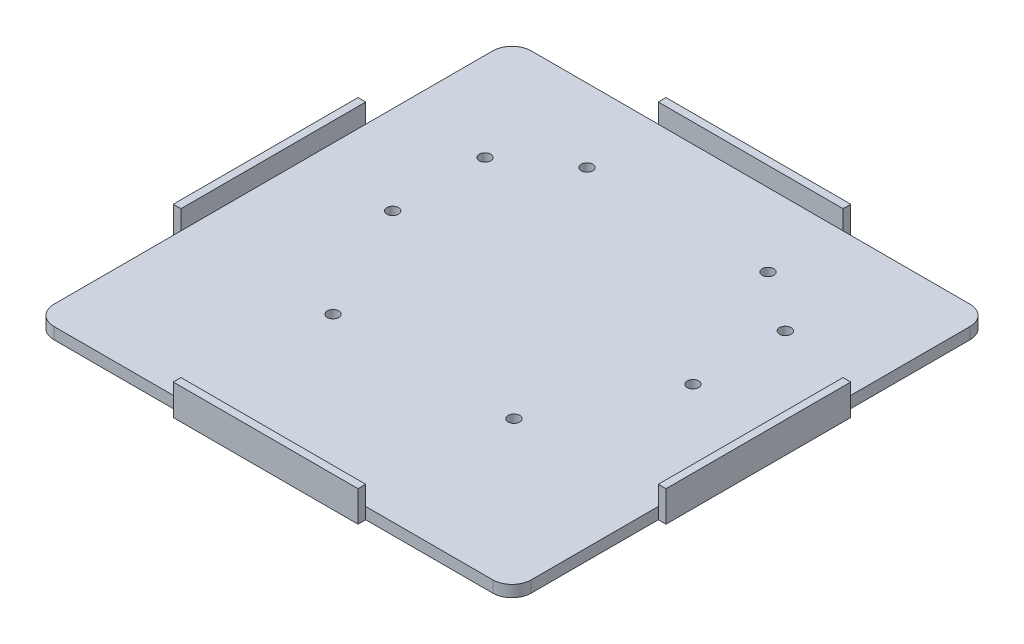
SolidWorks part; units mm, degrees
ref_plane "前视基准面" through (0, 0, 0) normal (0, 0, 1) x (1, 0, 0)
ref_plane "上视基准面" through (0, 0, 0) normal (0, 1, 0) x (1, 0, 0)
ref_plane "右视基准面" through (0, 0, 0) normal (1, 0, 0) x (0, 0, -1)
other "Configuration Table"
sketch "草图1" plane through (0, 0, 0) normal (0, 1, 0) x (1, 0, 0)
  line L1 (-64, 64) -> (64, 64)
  line L2 (-64, 64) -> (-64, -64)
  line L3 (-64, -64) -> (64, -64)
  line L4 (64, 64) -> (64, -64)
  line L5 (-64, 64) -> (64, -64) construction
  line L6 (-64, -64) -> (64, 64) construction
  point P0 (0, 0)
extrude "凸台-拉伸1" add sketch "草图1" along normal blind 8
sketch "草图2" plane through (0, 8, 0) normal (0, 1, 0) x (1, 0, 0)
  line L0 (-67.8405, 62) -> (72.7837, 62) construction
  line L1 (64, 64) -> (-64, 64) construction
  line L2 (-71.2496, 0) -> (72.7837, 0) construction
  line L3 (-67.8405, -62) -> (72.7837, -62) construction
  line L4 (0, 66.3065) -> (0, -71.761) construction
  line L5 (-24, 69.2042) -> (-24, -71.761) construction
  line L6 (-64, 64) -> (-64, -64) construction
  line L7 (24, 71.4201) -> (24, -73.8064) construction
  line L8 (64, -64) -> (64, 64) construction
  line L9 (-62, 69.2042) -> (-62, -69.886) construction
  line L10 (-71.2496, 24) -> (74.9996, 24) construction
  line L11 (-71.2496, -24) -> (74.9996, -24) construction
  line L12 (-64, 64) -> (-64, 24)
  line L13 (-64, 24) -> (-62, 24)
  line L14 (-62, 24) -> (-62, 62)
  line L15 (-62, 62) -> (-24, 62)
  line L16 (-24, 62) -> (-24, 64)
  line L17 (-24, 64) -> (-64, 64)
  line L18 (-64, -24) -> (-62, -24)
  line L19 (-64, -64) -> (-64, -24)
  line L20 (-62, -24) -> (-62, -62)
  line L21 (-62, -62) -> (-24, -62)
  line L22 (-24, -62) -> (-24, -64)
  line L23 (-24, -64) -> (-64, -64)
  line L24 (24, -62) -> (24, -64)
  line L25 (64, 24) -> (62, 24)
  line L26 (24, 62) -> (24, 64)
  line L27 (24, 64) -> (64, 64)
  line L28 (62, 62) -> (24, 62)
  line L29 (64, 64) -> (64, 24)
  line L30 (62, 24) -> (62, 62)
  line L31 (24, -64) -> (64, -64)
  line L32 (62, -62) -> (24, -62)
  line L33 (64, -64) -> (64, -24)
  line L34 (64, -24) -> (62, -24)
  line L35 (62, -24) -> (62, -62)
  dimension "D1" = 2
  dimension "D2" = 40
  dimension "D3" = 40
  dimension "D4" = 2
  dimension "D5" = 40
extrude "切除-拉伸1" cut sketch "草图2" against normal blind 8
sketch "草图3" plane through (0, 8, 0) normal (0, 1, 0) x (1, 0, 0)
  line L0 (-62, 62) -> (62, 62) construction
  line L1 (62, 62) -> (62, -62) construction
  line L2 (62, -62) -> (-62, -62) construction
  line L3 (-62, -62) -> (-62, 62) construction
  line L4 (-62, 62) -> (62, 62)
  line L5 (62, 62) -> (62, -62)
  line L6 (62, -62) -> (-62, -62)
  line L7 (-62, -62) -> (-62, 62)
extrude "切除-拉伸2" cut sketch "草图3" against normal blind 5
fillet "圆角1" radius 5 1 edges at (-62, 1.5, 62)
fillet "圆角2" radius 5 1 edges at (62, 1.5, 62)
fillet "圆角3" radius 5 1 edges at (62, 1.5, -62)
fillet "圆角4" radius 5 1 edges at (-62, 1.5, -62)
sketch "草图4" plane through (0, 0, 0) normal (0, -1, 0) x (1, 0, 0)
  line L0 (0, 68.6928) -> (0, -70.2269) construction
  line L1 (-23.5, 68.6928) -> (-23.5, -72.7837) construction
  line L2 (23.5, 68.6928) -> (23.5, -72.7837) construction
  line L3 (-75.6814, -43) -> (75.3405, -43) construction
  line L4 (-57, -62) -> (-24, -62) construction
  line L5 (-73.8064, 23) -> (79.2609, 23) construction
  line L6 (-39, 68.6928) -> (-39, -72.7837) construction
  line L8 (-88.8063, -32) -> (75.3405, -32) construction
  line L9 (-88.8063, -8) -> (86.2495, -8) construction
  circle A0 centre (-23.5, -43) radius 1.5
  circle A1 centre (23.5, -43) radius 1.5
  circle A2 centre (-23.5, 23) radius 1.5
  circle A3 centre (23.5, 23) radius 1.5
  circle A6 centre (-39, -32) radius 1.5
  circle A7 centre (39, -32) radius 1.5
  circle A8 centre (-39, -8) radius 1.5
  circle A9 centre (39, -8) radius 1.5
  dimension "D3" = 85
  dimension "D4" = 39
  dimension "D5" = 11
  dimension "D6" = 24
  dimension "D1" = 23.5
  dimension "D2" = 19
extrude "切除-拉伸3" cut sketch "草图4" against normal blind 4
